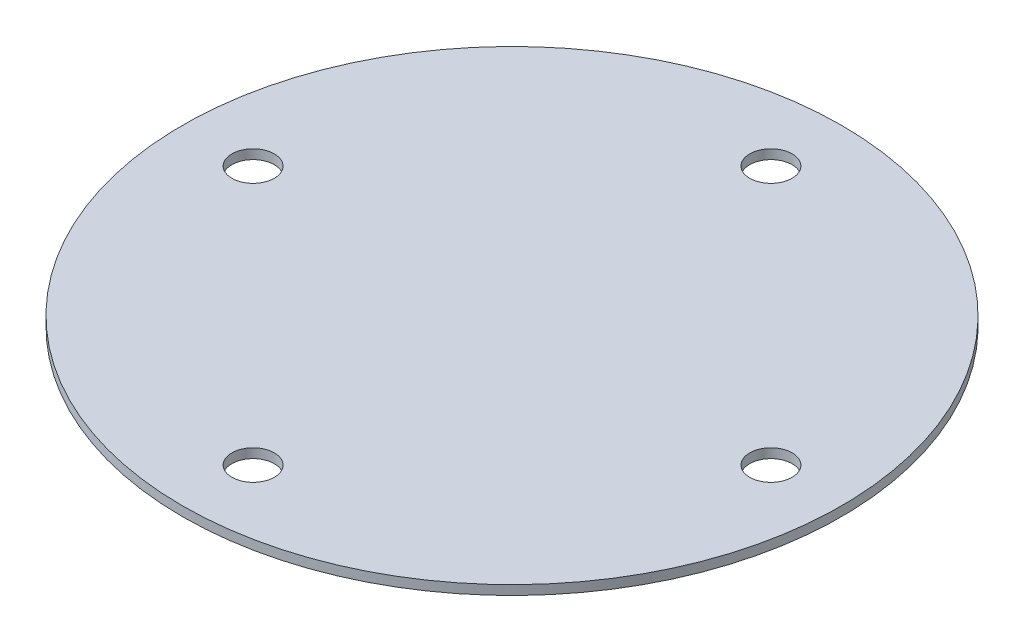
SolidWorks part; units mm, degrees
ref_plane "Front Plane" through (0, 0, 0) normal (0, 0, 1) x (1, 0, 0)
ref_plane "Top Plane" through (0, 0, 0) normal (0, 1, 0) x (1, 0, 0)
ref_plane "Right Plane" through (0, 0, 0) normal (1, 0, 0) x (0, 0, -1)
sketch "Sketch1" plane through (0, 0, 0) normal (0, 1, 0) x (1, 0, 0)
  circle A0 centre (0, 0) radius 35
  circle A1 centre (0, 0) radius 20
  dimension "D1" = 70
  dimension "D2" = 40
extrude "Boss-Extrude1" add sketch "Sketch1" along normal blind 1
sketch "Sketch3" plane through (0, 0, 0) normal (0, 1, 0) x (1, 0, 0)
  circle A0 centre (0, 0) radius 20
extrude "Boss-Extrude2" add sketch "Sketch3" along normal up to surface (1 mm away) up to face at (0, 1, 35)
sketch "Sketch4" plane through (0, 1, 0) normal (0, 1, 0) x (1, 0, 0)
  circle A0 centre (0, 27.5) radius 2.25
  circle A1 centre (27.5, 0) radius 2.25
  circle A2 centre (0, -27.5) radius 2.25
  circle A3 centre (-27.5, 0) radius 2.25
  point P12 (0, 0)
  dimension "D1" = 4.5
  dimension "D2" = 27.5
  dimension "D3" = 4
extrude "Cut-Extrude1" cut sketch "Sketch4" against normal up to next
